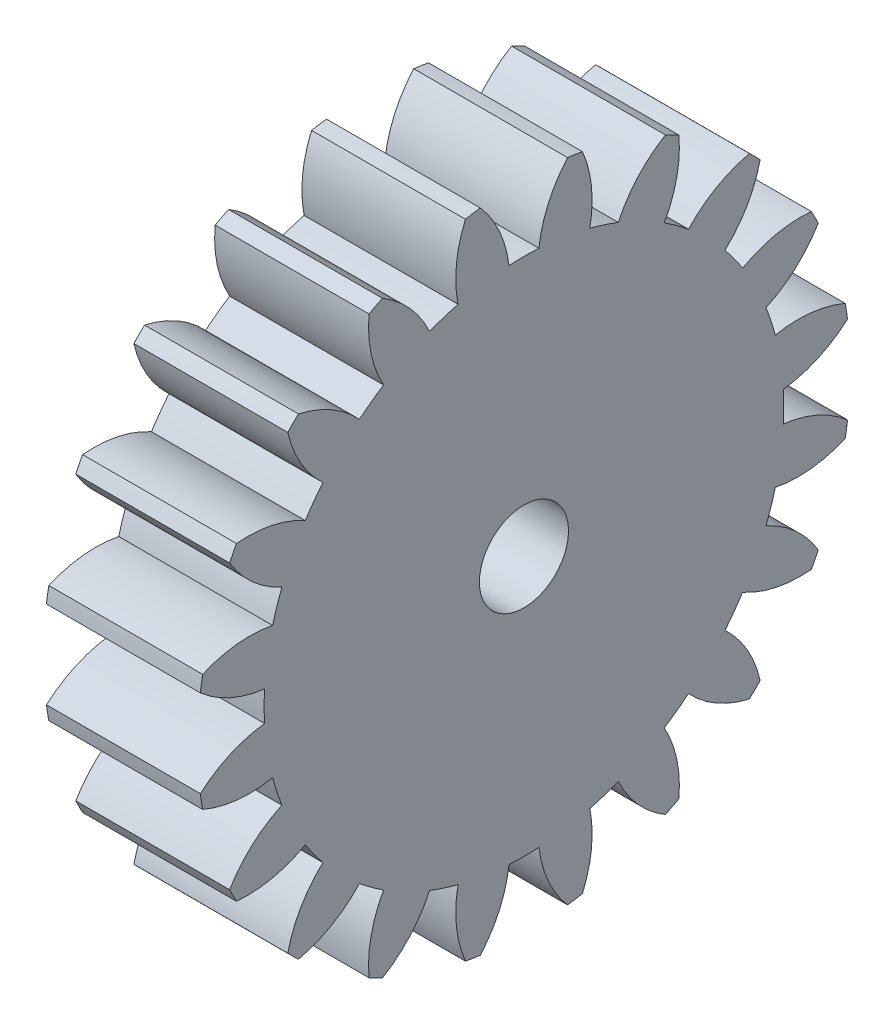
SolidWorks part; units mm, degrees
material "Nickel"
ref_plane "Plane1" through (0, 0, 0) normal (0, 0, 1) x (1, 0, 0)
ref_plane "Plane2" through (0, 0, 0) normal (0, 1, 0) x (1, 0, 0)
ref_plane "Plane3" through (0, 0, 0) normal (1, 0, 0) x (0, 0, -1)
sketch "HoldingSke" plane through (0, 0, 0) normal (0, 1, 0) x (1, 0, 0)
  line L0 (0, 0) -> (572.8366, -208.4955)
  line L1 (-15, 0) -> (100, 0) construction
  line L2 (0, 0) -> (-2.1039, 2.3779)
  line L3 (0, 0) -> (-11.863, 4.5341)
  line L4 (0, 0) -> (8.1152, 2.9537)
  line L5 (0, 0) -> (-47.5972, -17.7524)
  line L6 (0, 0) -> (-4.548, -3.0686)
  line L7 (-2.1039, 2.3779) -> (8.8308, 51.9871)
  line L8 (-76.2, 54.61) -> (-72.771, 54.61)
  line L9 (-71.009, 38.7566) -> (-53.1078, 45.2721)
  line L10 (-76.2, 71.12) -> (104.1128, 71.12)
  line L11 (0, 0) -> (-5.4864, 0)
  line L12 (-76.2, 101.6) -> (-76.1573, 101.6)
  line L13 (24.9733, 27.94) -> (52.9518, 28.4284)
  line L14 (24.9733, 27.94) -> (25.0241, 27.9398)
  line L15 (24.9733, 27.94) -> (100.4021, 29.52)
  circle A0 centre (0, 0) radius 1.5875
  circle A1 centre (0, 0) radius 9.2625
  circle A2 centre (0, 0) radius 38.1
  circle A3 centre (0, 0) radius 1.5875
  dimension "MHD" = 18.5251
  dimension "Hub_dia" = 76.2
  dimension "Bore" = 3.175
  dimension "MBD" = 3.175
  dimension "Num_teeth" = 20
  dimension "Pitch" = 609.6
  dimension "Overall_len" = 50.8
  dimension "Show_teeth" = 20
  dimension "Thickness" = 5.4864
  dimension "OAL" = 50.8001
  dimension "T_dim" = 3.429
  dimension "Ap" = 20
  dimension "H" = 19.05
  dimension "Pitch_radius" = 180.3128
  dimension "Width" = 5.4864
  dimension "Backlash" = 0.0427
  dimension "Addendum_fac" = 1
  dimension "Dedendum_fac" = 1.2
  dimension "Clearance_fac" = 0.2
  dimension "Dedendum_add" = 0.0508
sketch "BasProSke" plane through (0, 0, 0) normal (0, 1, 0) x (1, 0, 0)
  line L0 (-10, 0) -> (60, 0) construction
  line L1 (0, 0) -> (0, 11.6417)
  line L2 (0, 0) -> (5.4864, 0)
  line L3 (5.4864, 0) -> (5.4864, 11.6417)
  line L4 (5.4864, 11.6417) -> (0, 11.6417)
  dimension "Thickness" = 5.4864
  dimension "Diameter" = 23.2833
revolve "Base-Revolve" add sketch "BasProSke" angle 360 about L0
sketch "TooCutSke" plane through (0, 0, 0) normal (1, 0, 0) x (0, 0, -1)
  line L1 (0, 0) -> (0, 107) construction
  line L2 (0, 0) -> (-0.905, 10.5446) construction
  line L3 (0, 0) -> (-3.3027, 20.8527) construction
  line L4 (-0.905, 10.5446) -> (-1.6514, 10.4264) construction
  arc A0 (0.5332, 9.2472) -> (-0.5332, 9.2472) centre (0, 0) ccw
  arc A1 (1.5753, 11.5602) -> (-1.5753, 11.5602) centre (0, 0) ccw
  circle A2 centre (0, 0) radius 10.5833 construction
  circle A3 centre (0, 0) radius 9.9451 construction
  arc A4 (-0.5332, 9.2472) -> (-1.5753, 11.5602) centre (-4.7366, 8.7447) ccw
  arc A5 (1.5753, 11.5602) -> (0.5332, 9.2472) centre (4.7366, 8.7447) ccw
  dimension "Root_dia" = 18.5251
  dimension "Overcut_dia" = 23.3341
  dimension "Pitch_dia" = 21.1667
  dimension "Base_dia" = 19.8902
  dimension "Flank_rad" = 4.2333
  dimension "Half_ang" = 9
  dimension "Half_CT" = 0.7557
extrude "ToothCut" cut sketch "TooCutSke" along normal through all
fillet "Breaks" [suppressed] radius 0.0212
fillet "RootFillets" [suppressed] radius 0.2625
pattern_circular "TeethCuts" count 20 every 18 about axis through (-10, 0, 0) along (1, 0, 0) of "ToothCut", "RootFillets", "Breaks"
sketch "HubNeaOneSke" plane through (0, 0, 0) normal (-1, 0, 0) x (0, 0, 1)
  circle A0 centre (0, 0) radius 9.2625
  dimension "Diameter" = 18.5251
extrude "HubNearOne" [suppressed] add sketch "HubNeaOneSke" along normal blind 45.3137
sketch "HubNeaBotSke" plane through (0, 0, 0) normal (-1, 0, 0) x (0, 0, 1)
  circle A0 centre (0, 0) radius 9.2625
  dimension "Diameter" = 18.5251
extrude "HubNearBoth" [suppressed] add sketch "HubNeaBotSke" along normal blind 22.6568
ref_plane "FarPln" through (5.4864, 0, 0) normal (1, 0, 0) x (0, 0, -1)
sketch "HubFarSke" plane through (5.4864, 0, 0) normal (1, 0, 0) x (0, 0, -1)
  circle A0 centre (0, 0) radius 9.2625
  dimension "Diameter" = 18.5251
extrude "HubFar" [suppressed] add sketch "HubFarSke" along normal blind 22.6568
sketch "BorSke" plane through (0, 0, 0) normal (1, 0, 0) x (0, 0, -1)
  circle A0 centre (0, 0) radius 1.5875
  dimension "Diameter" = 3.175
extrude "Bore" cut sketch "BorSke" along normal mid plane 101.6001
sketch "KeySke" plane through (0, 0, 0) normal (1, 0, 0) x (0, 0, -1)
  line L0 (-0.127, 0) -> (-0.127, 1.8415)
  line L1 (-0.127, 1.8415) -> (0.127, 1.8415)
  line L2 (0.127, 1.8415) -> (0.127, 0)
  line L3 (0, 0) -> (0, 34) construction
  line L4 (-0.127, 0) -> (0.127, 0)
  dimension "Offset" = 1.8415
  dimension "Width" = 0.254
extrude "Keyway" [suppressed] cut sketch "KeySke" along normal mid plane 101.6001
pattern_circular "Keyway2" [suppressed] count 2 every 90 about axis through (-10, 0, 0) along (1, 0, 0)
equation "' \"Pitch@HoldingSke\" = 4"
equation "' \"Num_teeth@HoldingSke\" = 12"
equation "' \"Ap@HoldingSke\" =  20"
equation "' \"Ap@HoldingSke\" = 20"
equation "' \"Width@HoldingSke\" = 0.5"
equation "' \"Hub_dia@HoldingSke\"= 1"
equation "' \"Hub_dia@HoldingSke\" = 1"
equation "' \"Overall_len@HoldingSke\" = 1.0"
equation "' \"Bore@HoldingSke\" = 0.75"
equation "' \"T_dim@HoldingSke\" = 0.85"
equation "' \"Width@KeySke\" = 0.25"
equation "' \"Show_teeth@HoldingSke\" = 13"
equation "' \"Backlash@HoldingSke\" = 0.009"
equation "' \"Addendum_fac@HoldingSke\" = 1.0"
equation "' \"Dedendum_fac@HoldingSke\" = 1.25"
equation "' \"Dedendum_add@HoldingSke\" = 0.00005"
equation "' \"Clearance_fac@HoldingSke\" = 0.25"
equation "' \"Pitch@HoldingSke\" = 0.5"
equation "' \"Num_teeth@HoldingSke\" = 23"
equation "' \"Show_teeth@HoldingSke\" = 23"
equation "' \"Backlash@HoldingSke\" = 0.0375"
equation "\"Overcut_dia@TooCutSke\" = (\"Num_teeth@HoldingSke\" + 2 * \"Addendum_fac@HoldingSke\") / \"Pitch@HoldingSke\" + 0.002"
equation "\"Pitch_dia@TooCutSke\" = \"Num_teeth@HoldingSke\" / \"Pitch@HoldingSke\""
equation "\"Base_dia@TooCutSke\" = \"Num_teeth@HoldingSke\" / \"Pitch@HoldingSke\" * cos((\"Ap@HoldingSke\"  * 3.14159265 / 180))"
equation "\"Root_dia@TooCutSke\" = (\"Num_teeth@HoldingSke\" + 2) / \"Pitch@HoldingSke\" - 2 * (\"Addendum_fac@HoldingSke\" + \"Dedendum_fac@HoldingSke\") / \"Pitch@HoldingSke\" - \"Dedendum_add@HoldingSke\" * 2"
equation "\"Half_ang@TooCutSke\" = 180 / \"Num_teeth@HoldingSke\""
equation "\"Half_CT@TooCutSke\" = \"Num_teeth@HoldingSke\" / \"Pitch@HoldingSke\" * sin((3.14159265 / 2 / \"Num_teeth@HoldingSke\")) / 2 - 7 * \"Backlash@HoldingSke\" / 4"
equation "\"Flank_rad@TooCutSke\" = \"Num_teeth@HoldingSke\" / \"Pitch@HoldingSke\" / 5"
equation "\"Radius@RootFillets\" = \"Clearance_fac@HoldingSke\" / \"Pitch@HoldingSke\" + \"Dedendum_add@HoldingSke\""
equation "\"Break_rad@Breaks\" = 0.02 / \"Pitch@HoldingSke\""
equation "\"Thickness@HoldingSke\" = \"Width@HoldingSke\""
equation "\"OAL@HoldingSke\" = \"Thickness@HoldingSke\""
equation "\"MHD@HoldingSke\" = (\"Num_teeth@HoldingSke\" + 2) / \"Pitch@HoldingSke\" - 2 * (\"Addendum_fac@HoldingSke\" + \"Dedendum_fac@HoldingSke\")  / \"Pitch@HoldingSke\" - \"Dedendum_add@HoldingSke\" * 2"
equation "\"MBD@HoldingSke\" = (\"Num_teeth@HoldingSke\" + 2) / \"Pitch@HoldingSke\" - 2 * (\"Addendum_fac@HoldingSke\" + \"Dedendum_fac@HoldingSke\")  / \"Pitch@HoldingSke\" - \"Dedendum_add@HoldingSke\" * 2 - 0.002"
equation "\"MHD@HoldingSke\" = ((sgn( \"MHD@HoldingSke\" - \"Hub_dia@HoldingSke\" )-1)*( \"MHD@HoldingSke\" - \"Hub_dia@HoldingSke\" ))/-2+ \"Hub_dia@HoldingSke\""
equation "\"MBD@HoldingSke\" = ((sgn( \"MBD@HoldingSke\" - \"Bore@HoldingSke\" )-1)*( \"MBD@HoldingSke\" - \"Bore@HoldingSke\" ))/-2+ \"Bore@HoldingSke\""
equation "\"OAL@HoldingSke\" = ((sgn( \"OAL@HoldingSke\" - \"Overall_len@HoldingSke\" )+1)*( \"OAL@HoldingSke\" - \"Overall_len@HoldingSke\" ))/2 + \"Overall_len@HoldingSke\" + 0.000002"
equation "\"Num_teeth@TeethCuts\" = int( \"Show_teeth@HoldingSke\" ) + 1"
equation "\"Num_teeth@TeethCuts\" = ((sgn( \"Num_teeth@TeethCuts\" - \"Num_teeth@HoldingSke\" )-1)*( \"Num_teeth@TeethCuts\" - \"Num_teeth@HoldingSke\" ))/-2+ \"Num_teeth@HoldingSke\""
equation "\"Num_teeth@TeethCuts\" = ((sgn( \"Num_teeth@TeethCuts\" - 2.0)+1)*( \"Num_teeth@TeethCuts\" - 2.0))/2 +2.0"
equation "\"Angle@TeethCuts\" = 360.0 / \"Num_teeth@HoldingSke\""
equation "\"Diameter@BasProSke\" = (\"Num_teeth@HoldingSke\" + 2 * \"Addendum_fac@HoldingSke\") / \"Pitch@HoldingSke\""
equation "\"Thickness@BasProSke\"  = \"Thickness@HoldingSke\""
equation "' \"Fillet_rad@BasProSke\" =  \"Thickness@HoldingSke\" * 0.05"
equation "' \"Fillet_rad@BasProSke\" = \"Thickness@HoldingSke\" * 0.05"
equation "\"MHD@HoldingSke\" = ((sgn( \"MHD@HoldingSke\" - \"Root_dia@TooCutSke\" )-1)*( \"MHD@HoldingSke\" - \"Root_dia@TooCutSke\" ))/-2+ \"Root_dia@TooCutSke\""
equation "\"Diameter@HubNeaOneSke\" = \"MHD@HoldingSke\""
equation "\"Length@HubNearOne\" = \"OAL@HoldingSke\" - \"Thickness@BasProSke\""
equation "\"Diameter@HubNeaBotSke\" = \"MHD@HoldingSke\""
equation "\"Length@HubNearBoth\" = ( \"OAL@HoldingSke\" - \"Thickness@BasProSke\" ) / 2.0"
equation "\"Thickness@FarPln\" = \"Thickness@BasProSke\""
equation "\"Diameter@HubFarSke\" = \"MHD@HoldingSke\""
equation "\"Length@HubFar\" = ( \"OAL@HoldingSke\" - \"Thickness@BasProSke\" ) / 2.0"
equation "\"Diameter@BorSke\" = \"MBD@HoldingSke\""
equation "\"D1@Bore\" = \"OAL@HoldingSke\" * 2.0"
equation "\"D1@Keyway\" = \"OAL@HoldingSke\" * 2.0"
equation "\"Offset@KeySke\" = \"T_dim@HoldingSke\" - \"MBD@HoldingSke\" / 2.0"
